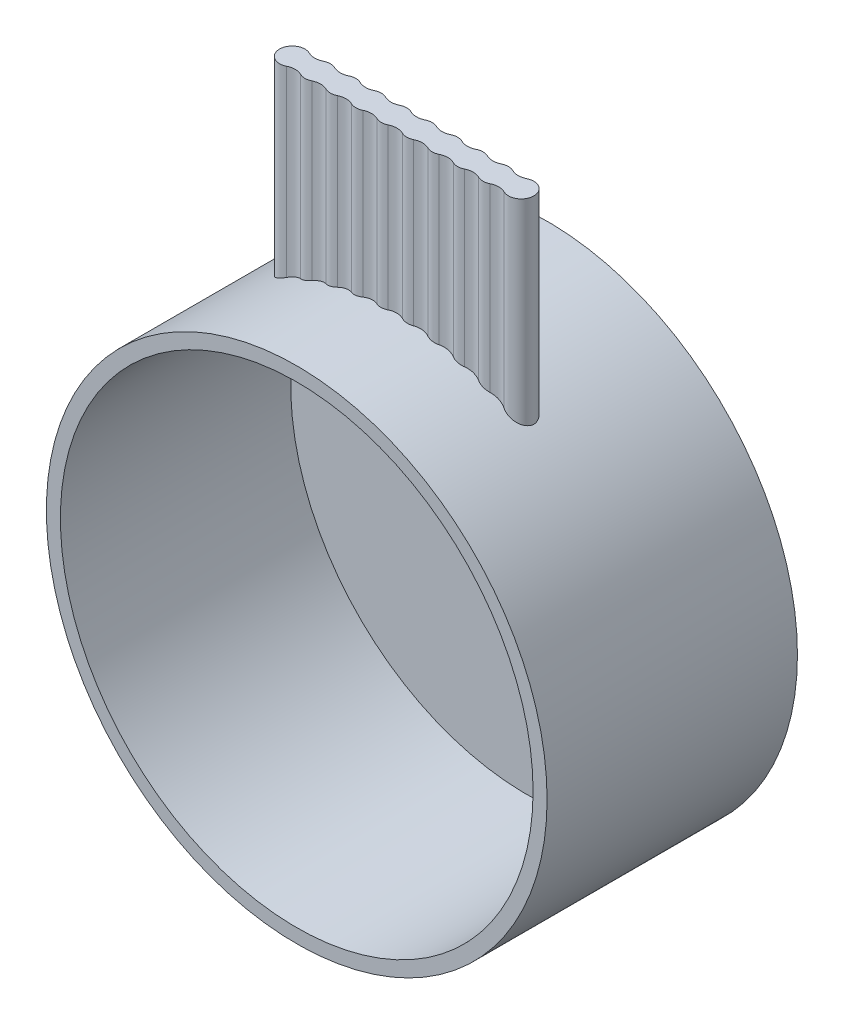
SolidWorks part; units mm, degrees
material "ABS"
ref_plane "Plan de face" through (0, 0, 0) normal (0, 0, 1) x (1, 0, 0)
ref_plane "Plan de dessus" through (0, 0, 0) normal (0, 1, 0) x (1, 0, 0)
ref_plane "Plan de droite" through (0, 0, 0) normal (1, 0, 0) x (0, 0, -1)
sketch "Esquisse1" plane through (0, 0, 0) normal (0, 0, 1) x (1, 0, 0)
  circle A0 centre (0, 0) radius 12.5
  dimension "D1" = 25
extrude "Boss.-Extru.1" add sketch "Esquisse1" along normal blind 1
sketch "Esquisse2" plane through (0, 0, 1) normal (0, 0, 1) x (1, 0, 0)
  circle A0 centre (0, 0) radius 11.8
  circle A1 centre (0, 0) radius 12.5
  dimension "D1" = 23.6
  dimension "D2" = 25
extrude "Boss.-Extru.2" add sketch "Esquisse2" along normal blind 11.5
ref_plane "Plan1" through (0, 12.5, 0) normal (0, 1, 0) x (-1, 0, 0)
sketch "Esquisse3" plane through (0, 12.5, 0) normal (0, 1, 0) x (-1, 0, 0)
  line L0 (5.4862, 7.2373) -> (-5.9438, 7.2373) construction
  arc A0 (5.2052, 6.6679) -> (5.2052, 7.8068) centre (5.4862, 7.2373) ccw
  arc A1 (4.4972, 7.8068) -> (3.9352, 7.8068) centre (4.2162, 7.2373) ccw
  arc A2 (3.2272, 7.8068) -> (2.6652, 7.8068) centre (2.9462, 7.2373) ccw
  arc A3 (1.9572, 7.8068) -> (1.3952, 7.8068) centre (1.6762, 7.2373) ccw
  arc A4 (0.6872, 7.8068) -> (0.1252, 7.8068) centre (0.4062, 7.2373) ccw
  arc A5 (-0.5828, 7.8068) -> (-1.1448, 7.8068) centre (-0.8638, 7.2373) ccw
  arc A6 (-1.8528, 7.8068) -> (-2.4148, 7.8068) centre (-2.1338, 7.2373) ccw
  arc A7 (-3.1228, 7.8068) -> (-3.6848, 7.8068) centre (-3.4038, 7.2373) ccw
  arc A8 (-4.3928, 7.8068) -> (-4.9548, 7.8068) centre (-4.6738, 7.2373) ccw
  arc A9 (-5.6628, 7.8068) -> (-5.6628, 6.6679) centre (-5.9438, 7.2373) ccw
  arc A10 (5.2052, 6.6679) -> (4.4972, 6.6679) centre (4.8512, 5.9505) ccw
  arc A11 (5.2052, 7.8068) -> (4.4972, 7.8068) centre (4.8512, 8.5242) cw
  arc A12 (3.9352, 6.6679) -> (3.2272, 6.6679) centre (3.5812, 5.9505) ccw
  arc A13 (3.9352, 7.8068) -> (3.2272, 7.8068) centre (3.5812, 8.5242) cw
  arc A14 (2.6652, 6.6679) -> (1.9572, 6.6679) centre (2.3112, 5.9505) ccw
  arc A15 (2.6652, 7.8068) -> (1.9572, 7.8068) centre (2.3112, 8.5242) cw
  arc A16 (1.3952, 6.6679) -> (0.6872, 6.6679) centre (1.0412, 5.9505) ccw
  arc A17 (1.3952, 7.8068) -> (0.6872, 7.8068) centre (1.0412, 8.5242) cw
  arc A18 (0.1252, 6.6679) -> (-0.5828, 6.6679) centre (-0.2288, 5.9505) ccw
  arc A19 (0.1252, 7.8068) -> (-0.5828, 7.8068) centre (-0.2288, 8.5242) cw
  arc A20 (-1.1448, 6.6679) -> (-1.8528, 6.6679) centre (-1.4988, 5.9505) ccw
  arc A21 (-1.1448, 7.8068) -> (-1.8528, 7.8068) centre (-1.4988, 8.5242) cw
  arc A22 (-2.4148, 6.6679) -> (-3.1228, 6.6679) centre (-2.7688, 5.9505) ccw
  arc A23 (-2.4148, 7.8068) -> (-3.1228, 7.8068) centre (-2.7688, 8.5242) cw
  arc A24 (-3.6848, 6.6679) -> (-4.3928, 6.6679) centre (-4.0388, 5.9505) ccw
  arc A25 (-3.6848, 7.8068) -> (-4.3928, 7.8068) centre (-4.0388, 8.5242) cw
  arc A26 (-4.9548, 6.6679) -> (-5.6628, 6.6679) centre (-5.3088, 5.9505) ccw
  arc A27 (-4.9548, 7.8068) -> (-5.6628, 7.8068) centre (-5.3088, 8.5242) cw
  arc A28 (3.9352, 6.6679) -> (4.4972, 6.6679) centre (4.2162, 7.2373) ccw
  arc A29 (2.6652, 6.6679) -> (3.2272, 6.6679) centre (2.9462, 7.2373) ccw
  arc A30 (1.3952, 6.6679) -> (1.9572, 6.6679) centre (1.6762, 7.2373) ccw
  arc A31 (0.1252, 6.6679) -> (0.6872, 6.6679) centre (0.4062, 7.2373) ccw
  arc A32 (-1.1448, 6.6679) -> (-0.5828, 6.6679) centre (-0.8638, 7.2373) ccw
  arc A33 (-2.4148, 6.6679) -> (-1.8528, 6.6679) centre (-2.1338, 7.2373) ccw
  arc A34 (-3.6848, 6.6679) -> (-3.1228, 6.6679) centre (-3.4038, 7.2373) ccw
  arc A35 (-4.9548, 6.6679) -> (-4.3928, 6.6679) centre (-4.6738, 7.2373) ccw
extrude "Boss.-Extru.4" add sketch "Esquisse3" along normal blind 8 and the other way blind 3
